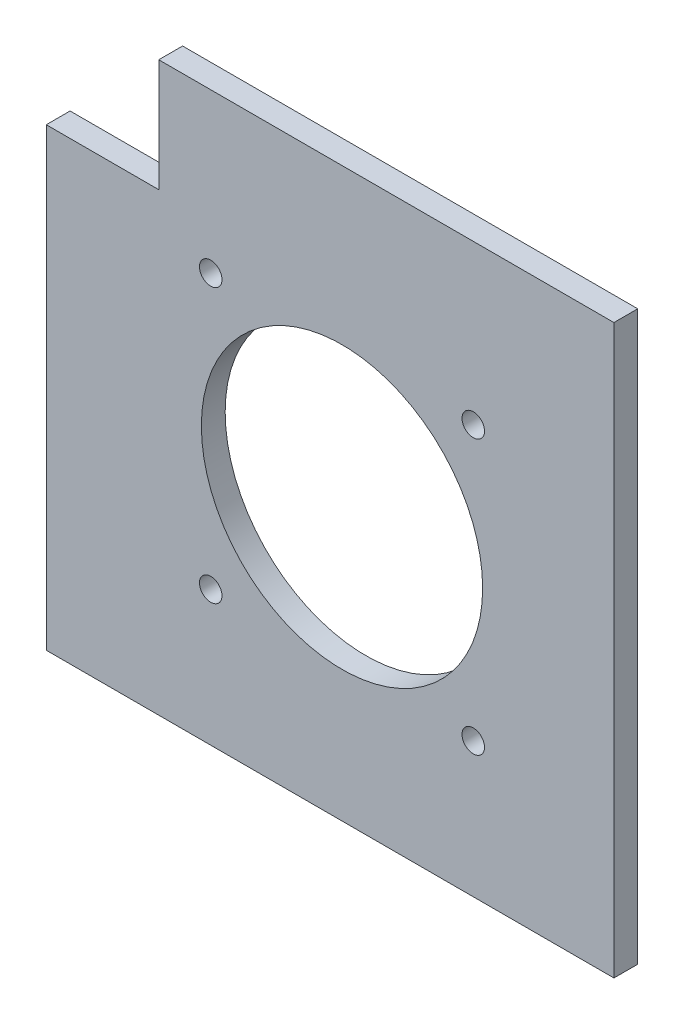
SolidWorks part; units mm, degrees
ref_plane "Alzado" through (0, 0, 0) normal (0, 0, 1) x (1, 0, 0)
ref_plane "Planta" through (0, 0, 0) normal (0, 1, 0) x (1, 0, 0)
ref_plane "Vista lateral" through (0, 0, 0) normal (1, 0, 0) x (0, 0, -1)
sketch "Croquis1" plane through (0, 0, 0) normal (0, 0, 1) x (1, 0, 0)
  line L0 (-20.3565, 25.4833) -> (100.9935, 25.4833) construction
  line L7 (100.9935, 25.4833) -> (100.9935, -125.8667) construction
  line L8 (100.9935, -125.8667) -> (-50.3565, -125.8667) construction
  line L9 (-50.3565, -125.8667) -> (-50.3565, -4.5167) construction
  line L10 (-50.3565, -4.5167) -> (-50.3565, -125.8667)
  line L11 (-50.3565, -4.5167) -> (-20.3565, -4.5167)
  line L12 (-20.3565, 25.4833) -> (-20.3565, -4.5167)
  line L13 (-50.3565, -125.8667) -> (100.9935, -125.8667)
  line L14 (100.9935, -125.8667) -> (100.9935, 25.4833)
  line L15 (100.9935, 25.4833) -> (-20.3565, 25.4833)
  point P0 (0, 0)
extrude "Saliente-Extruir1" add sketch "Croquis1" along normal blind 6.35
sketch "Croquis2" plane through (0, 0, 6.35) normal (0, 0, 1) x (1, 0, 0)
  line L0 (-50.3565, -10.8667) -> (-14.0065, -10.8667) construction
  line L1 (-50.3565, -4.5167) -> (-50.3565, -125.8667) construction
  line L2 (-14.0065, -10.8667) -> (70.9935, -95.8667) construction
  line L7 (-14.0065, -10.8667) -> (-14.0065, -16.8667) construction
  line L8 (-14.0065, -16.8667) -> (-6.5065, -16.8667) construction
  line L9 (-14.0065, -95.8667) -> (-14.0065, -89.8667) construction
  line L10 (-14.0065, -89.8667) -> (-6.5065, -89.8667) construction
  line L11 (28.4935, -95.8667) -> (28.4935, -73.1293) construction
  circle A0 centre (28.4935, -53.3667) radius 37.5
  circle A1 centre (-6.5065, -16.8667) radius 3
  circle A2 centre (-6.5065, -89.8667) radius 3
  circle A3 centre (63.4935, -16.8667) radius 3
  circle A4 centre (63.4935, -89.8667) radius 3
  dimension "D5" = 75
  dimension "D10" = 6
  dimension "D11" = 6
  dimension "D1" = 6.35
  dimension "D2" = 6.35
  dimension "D3" = 85
  dimension "D4" = 85
  dimension "D6" = 6
  dimension "D7" = 7.5
  dimension "D8" = 7.5
  dimension "D9" = 6
extrude "Cortar-Extruir1" cut sketch "Croquis2" against normal blind 6.35
